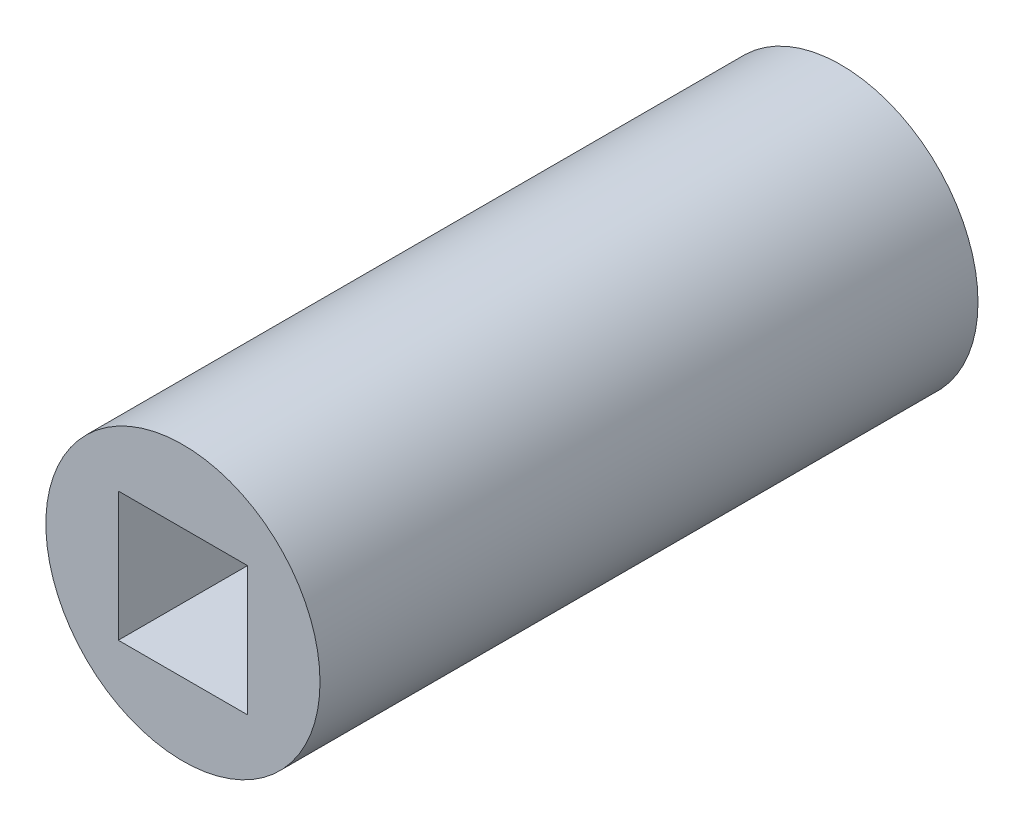
SolidWorks part; units mm, degrees
ref_plane "Front Plane" through (0, 0, 0) normal (0, 0, 1) x (1, 0, 0)
ref_plane "Top Plane" through (0, 0, 0) normal (0, 1, 0) x (1, 0, 0)
ref_plane "Right Plane" through (0, 0, 0) normal (1, 0, 0) x (0, 0, -1)
sketch "Sketch1" plane through (0, 0, 0) normal (0, 0, 1) x (1, 0, 0)
  circle A0 centre (0, 0) radius 3.75
  dimension "D1" = 7.5
extrude "Boss-Extrude1" add sketch "Sketch1" along normal blind 18
sketch "Sketch2" plane through (0, 0, 18) normal (0, 0, 1) x (1, 0, 0)
  line L1 (-1.7678, -1.7678) -> (1.7678, -1.7678)
  line L2 (-1.7678, -1.7678) -> (-1.7678, 1.7678)
  line L3 (-1.7678, 1.7678) -> (1.7678, 1.7678)
  line L4 (1.7678, -1.7678) -> (1.7678, 1.7678)
  line L5 (-1.7678, -1.7678) -> (1.7678, 1.7678) construction
  line L6 (-1.7678, 1.7678) -> (1.7678, -1.7678) construction
  circle A0 centre (0, 0) radius 2.5 construction
  point P0 (0, 0)
  point P8 (0, 0)
  dimension "D2" = 5
extrude "Cut-Extrude1" cut sketch "Sketch2" against normal blind 10
sketch "Sketch3" plane through (0, 0, 0) normal (0, 0, -1) x (-1, 0, 0)
  line L1 (-1.05, -2.5) -> (1.05, -2.5)
  line L2 (-1.05, -2.5) -> (-1.05, 2.5)
  line L3 (-1.05, 2.5) -> (1.05, 2.5)
  line L4 (1.05, -2.5) -> (1.05, 2.5)
  line L5 (-1.05, -2.5) -> (1.05, 2.5) construction
  line L6 (-1.05, 2.5) -> (1.05, -2.5) construction
  line L7 (-2.5, -1.05) -> (2.5, -1.05)
  line L8 (-2.5, -1.05) -> (-2.5, 1.05)
  line L9 (-2.5, 1.05) -> (2.5, 1.05)
  line L10 (2.5, -1.05) -> (2.5, 1.05)
  line L11 (-2.5, -1.05) -> (2.5, 1.05) construction
  line L12 (-2.5, 1.05) -> (2.5, -1.05) construction
  point P0 (0, 0)
  point P6 (0, 0)
  dimension "D1" = 5
  dimension "D2" = 2.1
extrude "Cut-Extrude2" cut sketch "Sketch3" against normal blind 8 contours L2 L9 L4 L3 | L9 L2 L7 L4 | L7 L10 L9 L4 | L7 L2 L1 L4 | L9 L8 L7 L2
